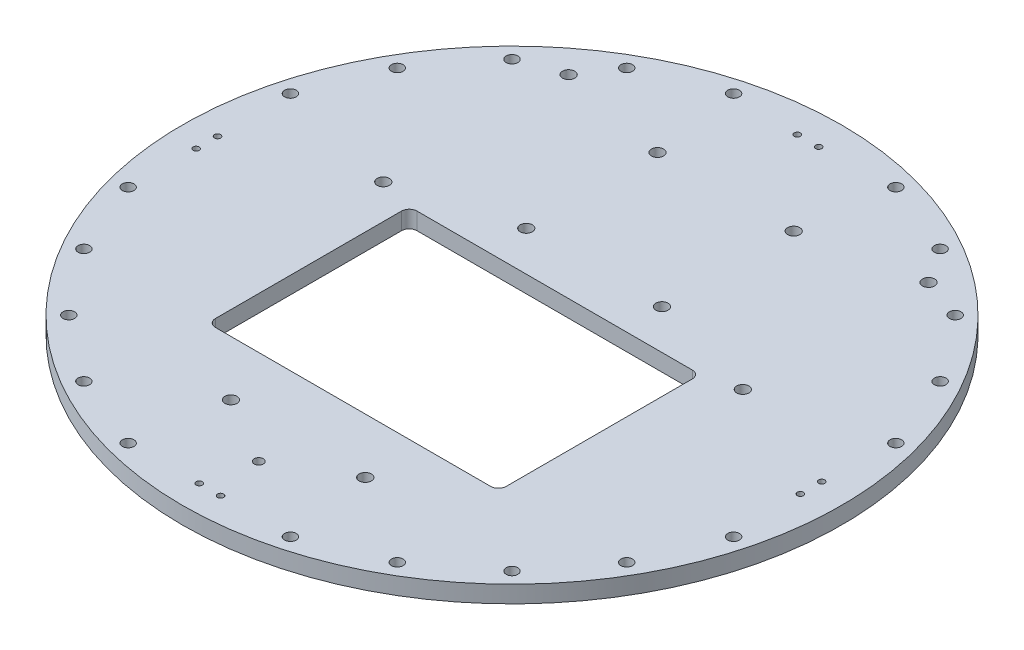
SolidWorks part; units mm, degrees
material "Acrylique (impact moyen-haut)"
ref_plane "Plan de face" through (0, 0, 0) normal (0, 0, 1) x (1, 0, 0)
ref_plane "Plan de dessus" through (0, 0, 0) normal (0, 1, 0) x (1, 0, 0)
ref_plane "Plan de droite" through (0, 0, 0) normal (1, 0, 0) x (0, 0, -1)
sketch "Esquisse1" plane through (0, 0, 0) normal (0, 1, 0) x (1, 0, 0)
  circle A0 centre (0, 0) radius 107.95
  dimension "D1" = 215.9
extrude "Boss.-Extru.1" add sketch "Esquisse1" along normal blind 5.588
sketch "Esquisse2" plane through (0, 5.588, 0) normal (0, 1, 0) x (1, 0, 0)
  line L0 (0, 0) -> (0, 102.6583) construction
  circle A1 centre (26.5699, 99.1603) radius 1.905
  circle A2 centre (51.3292, 88.9047) radius 1.905
  circle A3 centre (72.5904, 72.5904) radius 1.905
  circle A4 centre (88.9047, 51.3292) radius 1.905
  circle A5 centre (99.1603, 26.5699) radius 1.905
  circle A7 centre (99.1603, -26.5699) radius 1.905
  circle A8 centre (88.9047, -51.3292) radius 1.905
  circle A9 centre (72.5904, -72.5904) radius 1.905
  circle A10 centre (51.3292, -88.9047) radius 1.905
  circle A11 centre (26.5699, -99.1603) radius 1.905
  circle A13 centre (-26.5699, -99.1603) radius 1.905
  circle A14 centre (-51.3292, -88.9047) radius 1.905
  circle A15 centre (-72.5904, -72.5904) radius 1.905
  circle A16 centre (-88.9047, -51.3292) radius 1.905
  circle A17 centre (-99.1603, -26.5699) radius 1.905
  circle A19 centre (-99.1603, 26.5699) radius 1.905
  circle A20 centre (-88.9047, 51.3292) radius 1.905
  circle A21 centre (-72.5904, 72.5904) radius 1.905
  circle A22 centre (-51.3292, 88.9047) radius 1.905
  circle A23 centre (-26.5699, 99.1603) radius 1.905
  point P53 (0, 0)
  dimension "D1" = 102.6583
extrude "Enlèv. mat.-Extru.1" cut sketch "Esquisse2" against normal blind 5.588
sketch "Esquisse3" plane through (0, 5.588, 0) normal (0, 1, 0) x (1, 0, 0)
  line L0 (0, -107.95) -> (0, -52.07) construction
  line L1 (-45.085, -52.07) -> (45.085, -52.07)
  line L2 (47.625, -49.53) -> (47.625, 11.43)
  line L3 (45.085, 13.97) -> (-45.085, 13.97)
  line L4 (-47.625, 11.43) -> (-47.625, -49.53)
  circle A0 centre (0, 0) radius 107.95 construction
  arc A1 (-45.085, -52.07) -> (-47.625, -49.53) centre (-45.085, -49.53) cw
  arc A2 (45.085, -52.07) -> (47.625, -49.53) centre (45.085, -49.53) ccw
  arc A3 (47.625, 11.43) -> (45.085, 13.97) centre (45.085, 11.43) ccw
  arc A4 (-45.085, 13.97) -> (-47.625, 11.43) centre (-45.085, 11.43) ccw
  point P12 (0, -52.07)
  point P14 (-47.625, -52.07)
  point P17 (47.625, -52.07)
  point P20 (47.625, 13.97)
  dimension "D4" = 2.54
  dimension "D1" = 55.88
  dimension "D2" = 95.25
  dimension "D3" = 66.04
extrude "Enlèv. mat.-Extru.2" cut sketch "Esquisse3" against normal blind 5.588
sketch "Esquisse5" plane through (0, 5.588, 0) normal (0, 1, 0) x (1, 0, 0)
  line L0 (0, -107.95) -> (0, -98.95) construction
  line L1 (0, -98.95) -> (-3.5, -98.95) construction
  circle A0 centre (0, 0) radius 107.95 construction
  circle A1 centre (-3.5, -98.95) radius 1
  circle A2 centre (3.5, -98.95) radius 1
  circle A3 centre (-98.95, 2.5) radius 1
  circle A4 centre (-98.95, -4.5) radius 1
  circle A5 centre (2.5, 97.95) radius 1
  circle A6 centre (-4.5, 97.95) radius 1
  circle A7 centre (97.95, -3.5) radius 1
  circle A8 centre (97.95, 3.5) radius 1
  point P25 (-0.5, -0.5)
  dimension "D3" = 2
  dimension "D1" = 9
  dimension "D2" = 3.5
  dimension "D4" = 4
extrude "Enlèv. mat.-Extru.3" cut sketch "Esquisse5" against normal through all
sketch "Esquisse6" plane through (0, 5.588, 0) normal (0, 1, 0) x (1, 0, 0)
  line L0 (0, -52.07) -> (0, -70.07) construction
  line L1 (-45.085, -52.07) -> (45.085, -52.07) construction
  line L2 (0, -70.07) -> (-22, -70.07) construction
  line L3 (0, -70.07) -> (22, -70.07) construction
  line L4 (0, 13.97) -> (0, 69.97) construction
  line L5 (0, 69.97) -> (-22.3, 69.97) construction
  line L6 (45.085, 13.97) -> (-45.085, 13.97) construction
  line L7 (-107.95, 0) -> (-58.95, 0) construction
  line L8 (-58.95, 0) -> (-58.95, 77.5) construction
  line L9 (-22.3, 69.97) -> (-22.3, 26.97) construction
  line L10 (-22.3, 26.97) -> (58.5731, 26.97) construction
  circle A0 centre (-22, -70.07) radius 2
  circle A1 centre (22, -70.07) radius 2
  circle A2 centre (0, 0) radius 107.95 construction
  circle A3 centre (-22.3, 69.97) radius 2
  circle A4 centre (22.3, 69.97) radius 2
  circle A5 centre (-58.95, 77.5) radius 2
  circle A6 centre (58.95, 77.5) radius 2
  circle A7 centre (-22.3, 26.97) radius 2
  circle A8 centre (22.15, 26.97) radius 2
  dimension "D3" = 4
  dimension "D5" = 4
  dimension "D8" = 4
  dimension "D11" = 4
  dimension "D13" = 22.15
  dimension "D1" = 18
  dimension "D2" = 22
  dimension "D4" = 22
  dimension "D6" = 22.3
  dimension "D7" = 56
  dimension "D9" = 49
  dimension "D10" = 77.5
  dimension "D12" = 43
extrude "Enlèv. mat.-Extru.4" cut sketch "Esquisse6" against normal through all
sketch "Esquisse7" plane through (0, 5.588, 0) normal (0, 1, 0) x (1, 0, 0)
  line L0 (46.8811, 13.2261) -> (58.8811, 13.2261) construction
  line L2 (58.8811, 13.2261) -> (58.8811, 16.7261) construction
  line L3 (0, 0) -> (0, 53.0473) construction
  arc A2 (47.625, 11.43) -> (45.085, 13.97) centre (45.085, 11.43) ccw construction
  circle A3 centre (58.8811, 16.7261) radius 2
  circle A4 centre (22.25, 24.97) radius 2 construction
  circle A5 centre (-58.8811, 16.7261) radius 2
  point P5 (46.8811, 13.2261)
  dimension "D1" = 12
  dimension "D2" = 3.5
extrude "Enlèv. mat.-Extru.5" cut sketch "Esquisse7" against normal through all
sketch "Esquisse8" plane through (0, 5.588, 0) normal (0, 1, 0) x (1, 0, 0)
  line L0 (0, -107.95) -> (0, -82.95) construction
  circle A0 centre (0, 0) radius 107.95 construction
  circle A1 centre (0, -82.95) radius 1.5
  dimension "D2" = 3
  dimension "D1" = 25
extrude "Enlèv. mat.-Extru.6" cut sketch "Esquisse8" against normal through all
